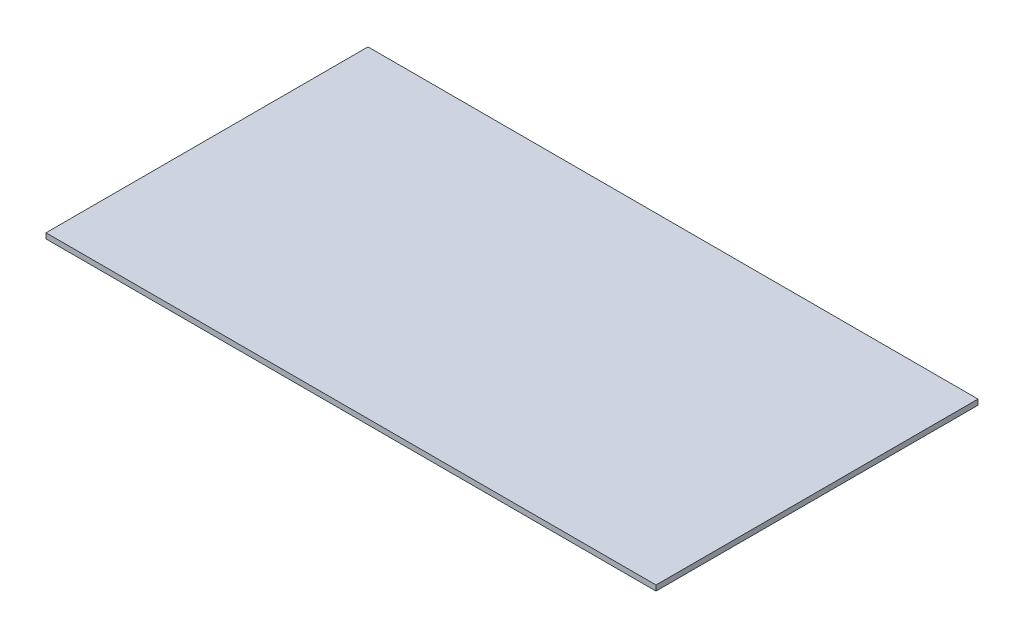
SolidWorks part; units mm, degrees
material "5052-H34"
ref_plane "Front Plane" through (0, 0, 0) normal (0, 0, 1) x (1, 0, 0)
ref_plane "Top Plane" through (0, 0, 0) normal (0, 1, 0) x (1, 0, 0)
ref_plane "Right Plane" through (0, 0, 0) normal (1, 0, 0) x (0, 0, -1)
sketch "Sketch1" plane through (0, 0, 0) normal (0, 0, 1) x (1, 0, 0)
  line L0 (-580.595, 4.4417) -> (-36.865, 4.4417)
  line L1 (-36.865, 4.4417) -> (-36.865, -0.3208)
  line L3 (-36.865, -0.3208) -> (-580.595, -0.3208)
  line L6 (-580.595, 4.4417) -> (-580.595, -0.3208)
  point P2 (-580.595, 4.4417)
extrude "Boss-Extrude1" add sketch "Sketch1" along normal blind 287
